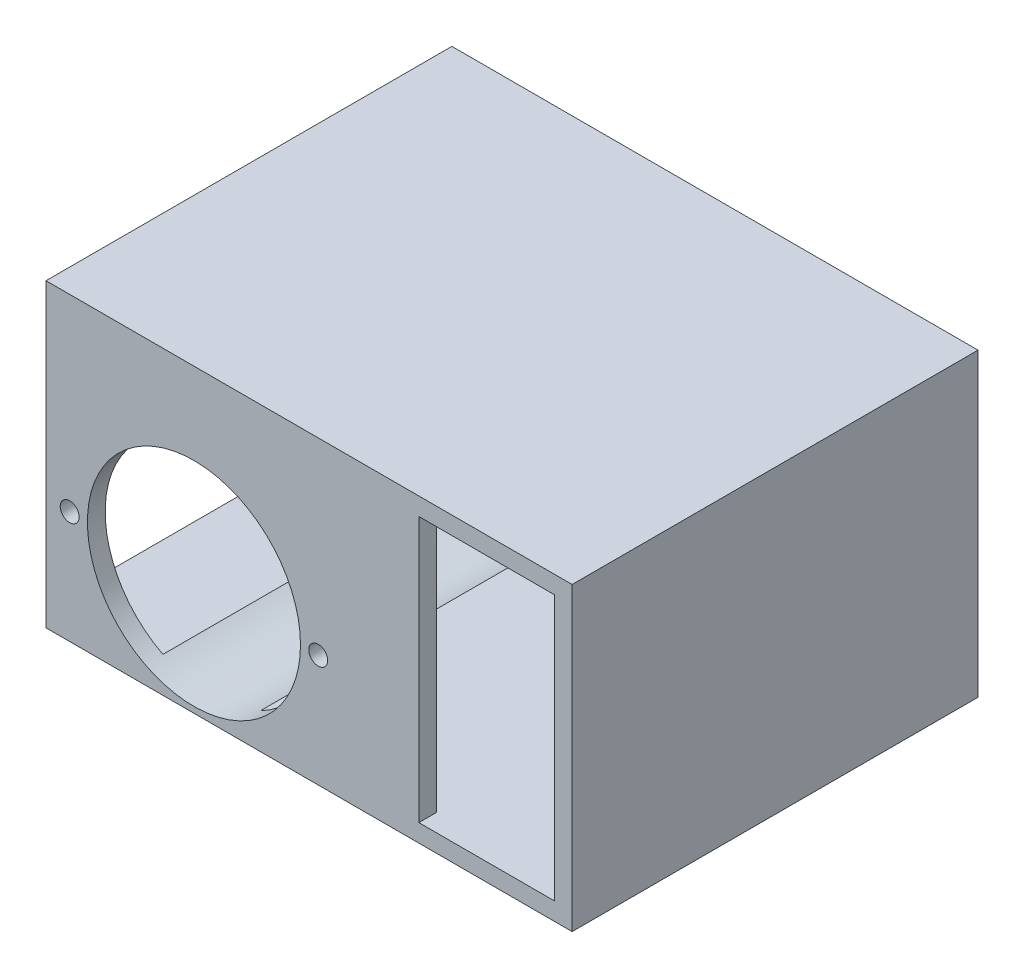
SolidWorks part; units mm, degrees
ref_plane "Front Plane" through (0, 0, 0) normal (0, 0, 1) x (1, 0, 0)
ref_plane "Top Plane" through (0, 0, 0) normal (0, 1, 0) x (1, 0, 0)
ref_plane "Right Plane" through (0, 0, 0) normal (1, 0, 0) x (0, 0, -1)
sketch "Sketch1" plane through (0, 0, 0) normal (0, 0, 1) x (1, 0, 0)
  line L1 (0, 0) -> (88.9, 0)
  line L2 (0, 0) -> (0, 50.8)
  line L3 (0, 50.8) -> (88.9, 50.8)
  line L4 (88.9, 0) -> (88.9, 50.8)
extrude "Boss-Extrude1" add sketch "Sketch1" along normal blind 68.58
sketch "Sketch2" plane through (0, 0, 68.58) normal (0, 0, 1) x (1, 0, 0)
  line L3 (63, 47.8) -> (85.9, 47.8)
  line L4 (63, 47.8) -> (63, 3)
  line L5 (63, 3) -> (85.9, 3)
  line L6 (85.9, 47.8) -> (85.9, 3)
  circle A0 centre (25, 19) radius 18
  circle A1 centre (4, 19) radius 1.6
  circle A2 centre (46, 19) radius 1.6
shell "Shell10" thickness 3
extrude "Cut-Extrude1" cut sketch "Sketch2" against normal blind 69
sketch "Sketch4" plane through (0, 0, 0) normal (-1, 0, 0) x (0, 0, 1)
  line L1 (3, 47.8) -> (65.58, 47.8)
  line L2 (3, 47.8) -> (3, 3)
  line L3 (3, 3) -> (65.58, 3)
  line L4 (65.58, 47.8) -> (65.58, 3)
extrude "Cut-Extrude2" cut sketch "Sketch4" against normal blind 10
